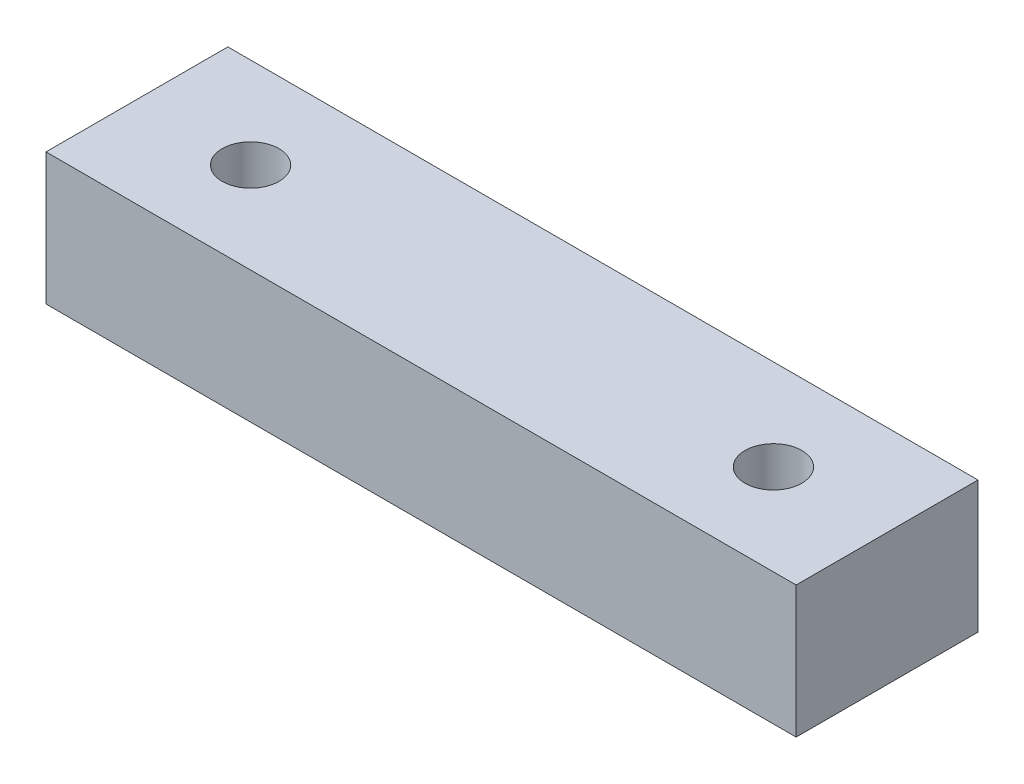
SolidWorks part; units mm, degrees
ref_plane "Front Plane" through (0, 0, 0) normal (0, 0, 1) x (1, 0, 0)
ref_plane "Top Plane" through (0, 0, 0) normal (0, 1, 0) x (1, 0, 0)
ref_plane "Right Plane" through (0, 0, 0) normal (1, 0, 0) x (0, 0, -1)
sketch "Sketch1" plane through (0, 0, 0) normal (0, 1, 0) x (1, 0, 0)
  line L1 (-41.91, -10.16) -> (41.91, -10.16)
  line L2 (-41.91, -10.16) -> (-41.91, 10.16)
  line L3 (-41.91, 10.16) -> (41.91, 10.16)
  line L4 (41.91, -10.16) -> (41.91, 10.16)
  line L5 (-41.91, -10.16) -> (41.91, 10.16) construction
  line L6 (-41.91, 10.16) -> (41.91, -10.16) construction
  circle A0 centre (-29.21, 0) radius 3.175
  circle A1 centre (29.21, 0) radius 3.175
  point P0 (0, 0)
  dimension "D3" = 6.35
  dimension "D4" = 6.35
  dimension "D5" = 58.42
  dimension "D6" = 12.7
  dimension "D7" = 12.7
  dimension "D1" = 20.32
  dimension "D2" = 83.82
extrude "Boss-Extrude1" add sketch "Sketch1" along normal blind 14.7225
